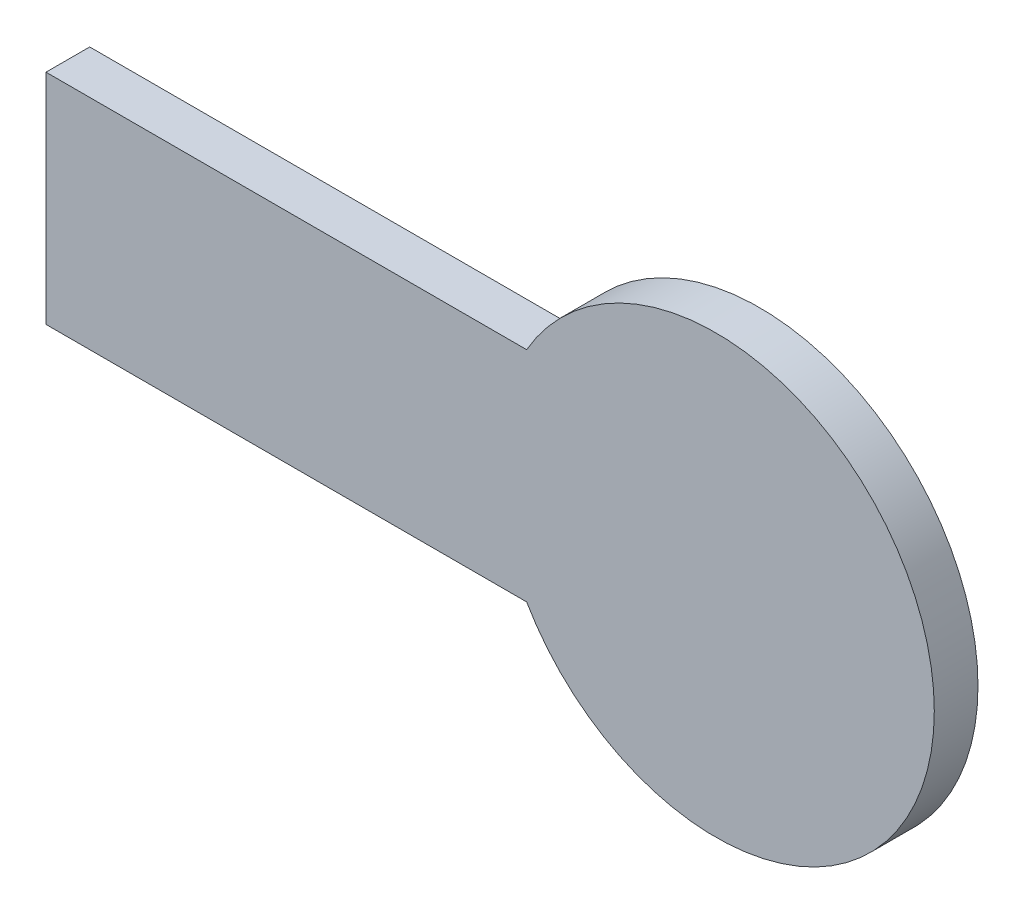
SolidWorks part; units mm, degrees
ref_plane "Front Plane" through (0, 0, 0) normal (0, 0, 1) x (1, 0, 0)
ref_plane "Top Plane" through (0, 0, 0) normal (0, 1, 0) x (1, 0, 0)
ref_plane "Right Plane" through (0, 0, 0) normal (1, 0, 0) x (0, 0, -1)
sketch "Sketch1" plane through (0, 0, 0) normal (0, 0, 1) x (1, 0, 0)
  line L0 (-153.3013, -25) -> (-153.3013, 25)
  line L1 (-153.3013, 25) -> (-43.3013, 25)
  line L2 (-153.3013, -25) -> (-43.3013, -25)
  arc A0 (-43.3013, -25) -> (-43.3013, 25) centre (0, 0) ccw
  point P6 (-153.3013, 0)
  point P9 (-153.3013, 25)
  dimension "D1" = 50
  dimension "D2" = 110
  dimension "D3" = 50
extrude "Boss-Extrude1" add sketch "Sketch1" along normal blind 10
